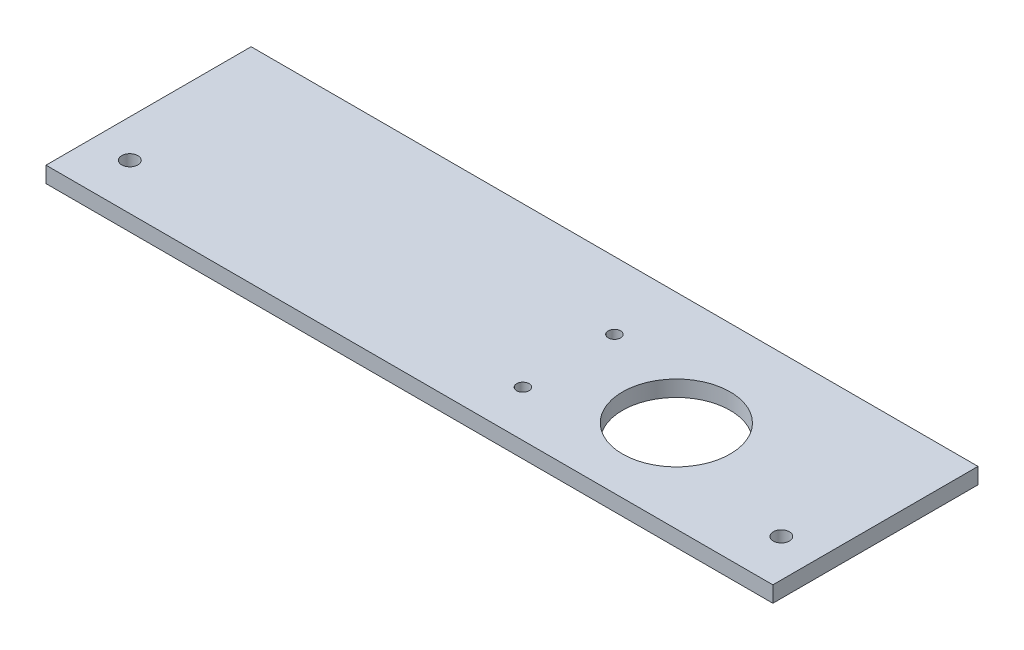
SolidWorks part; units mm, degrees
ref_plane "Front Plane" through (0, 0, 0) normal (0, 0, 1) x (1, 0, 0)
ref_plane "Top Plane" through (0, 0, 0) normal (0, 1, 0) x (1, 0, 0)
ref_plane "Right Plane" through (0, 0, 0) normal (1, 0, 0) x (0, 0, -1)
sketch "Sketch1" plane through (0, 0, 0) normal (0, 1, 0) x (1, 0, 0)
  line L0 (80, 25.5718) -> (80, 8.5718) construction
  line L1 (0, 0) -> (135, 0)
  line L2 (0, 0) -> (0, 38.1)
  line L3 (0, 38.1) -> (135, 38.1)
  line L4 (135, 0) -> (135, 38.1)
  circle A0 centre (80, 8.5718) radius 1.15
  circle A1 centre (80, 25.5718) radius 1.15
  circle A2 centre (100, 17.0718) radius 10
  point P11 (80, 17.0718)
  dimension "D3" = 2.3
  dimension "D6" = 20
  dimension "D1" = 38.1
  dimension "D2" = 135
  dimension "D4" = 17
  dimension "D5" = 55
  dimension "D7" = 20
  dimension "D8" = 8.5718
extrude "Boss-Extrude1" add sketch "Sketch1" along normal blind 2.9718
sketch "Sketch2" plane through (0, 2.9718, 0) normal (0, 1, 0) x (1, 0, 0)
  line L0 (0, 38.1) -> (0, 0) construction
  line L1 (135, 0) -> (135, 38.1) construction
  line L2 (0, 0) -> (135, 0) construction
  circle A0 centre (128, 8.5718) radius 1.5
  circle A1 centre (7, 8.5718) radius 1.5
  dimension "D1" = 3
  dimension "D2" = 7
  dimension "D3" = 7
  dimension "D4" = 8.5718
extrude "Cut-Extrude1" cut sketch "Sketch2" against normal through all
